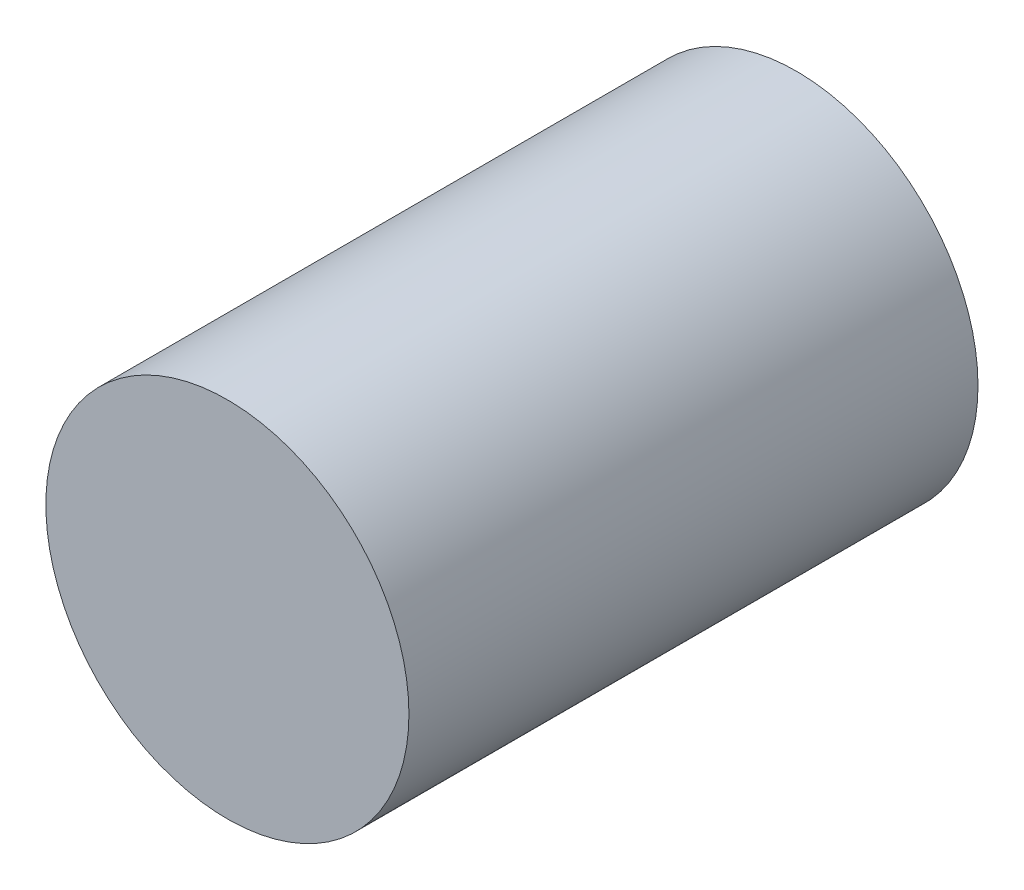
SolidWorks part; units mm, degrees
ref_plane "Front Plane" through (0, 0, 0) normal (0, 0, 1) x (1, 0, 0)
ref_plane "Top Plane" through (0, 0, 0) normal (0, 1, 0) x (1, 0, 0)
ref_plane "Right Plane" through (0, 0, 0) normal (1, 0, 0) x (0, 0, -1)
sketch "Sketch5" plane through (0, 0, 0) normal (0, 0, 1) x (1, 0, 0)
  circle A0 centre (0, 0) radius 95.7094
extrude "Boss-Extrude2" add sketch "Sketch5" against normal blind 300.0001
move or copy body "Body-Move/Copy2" bodies to move or copy 102 copy no translate (0, 0, 100)
